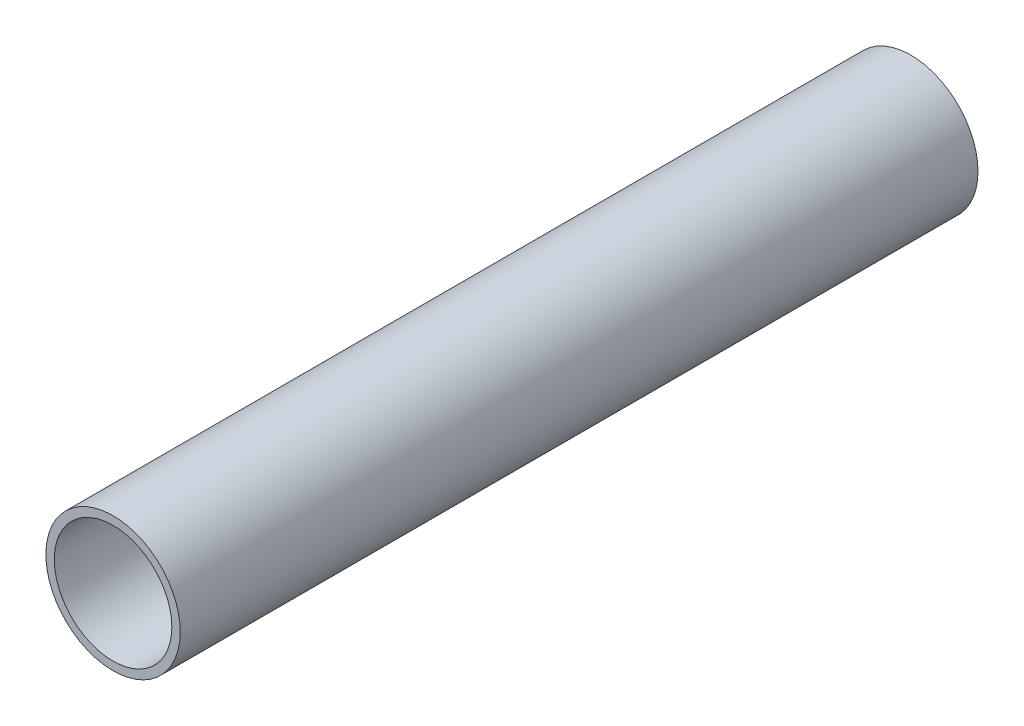
SolidWorks part; units mm, degrees
material "Thornel Mat VMA"
ref_plane "Front Plane" through (0, 0, 0) normal (0, 0, 1) x (1, 0, 0)
ref_plane "Top Plane" through (0, 0, 0) normal (0, 1, 0) x (1, 0, 0)
ref_plane "Right Plane" through (0, 0, 0) normal (1, 0, 0) x (0, 0, -1)
sketch "Sketch1" plane through (0, 0, 0) normal (0, 0, 1) x (1, 0, 0)
  circle A0 centre (0, 0) radius 7
  circle A1 centre (0, 0) radius 8
  dimension "D1" = 16
  dimension "D2" = 14
extrude "Boss-Extrude1" add sketch "Sketch1" along normal blind 95
